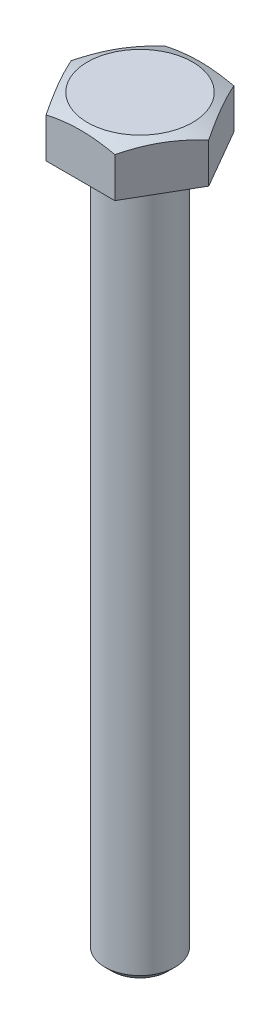
SolidWorks part; units mm, degrees
ref_plane "前视基准面" through (0, 0, 0) normal (0, 0, 1) x (1, 0, 0)
ref_plane "上视基准面" through (0, 0, 0) normal (0, 1, 0) x (1, 0, 0)
ref_plane "右视基准面" through (0, 0, 0) normal (1, 0, 0) x (0, 0, -1)
sketch "草图2" plane through (0, 0, 0) normal (0, 1, 0) x (1, 0, 0)
  line L1 (9.815, 0) -> (4.9075, 8.5)
  line L2 (4.9075, 8.5) -> (-4.9075, 8.5)
  line L3 (-4.9075, 8.5) -> (-9.815, 0)
  line L4 (-9.815, 0) -> (-4.9075, -8.5)
  line L5 (-4.9075, -8.5) -> (4.9075, -8.5)
  line L6 (4.9075, -8.5) -> (9.815, 0)
  circle A0 centre (0, 0) radius 8.5 construction
  dimension "D1" = 17
extrude "凸台-拉伸1" add sketch "草图2" along normal blind 6.7
sketch "草图3" plane through (0, 0, 0) normal (0, 0, 1) x (1, 0, 0)
  line L0 (-9.815, 5.7) -> (-7.5, 6.7)
  line L1 (-9.815, 6.7) -> (-9.815, 0) construction
  line L2 (-9.815, 6.7) -> (-4.9075, 6.7) construction
  line L3 (-7.5, 6.7) -> (-9.815, 6.7)
  line L4 (-9.815, 6.7) -> (-9.815, 5.7)
  line L5 (0, 0) -> (0, 6.7) construction
  line L6 (-4.9075, 0) -> (4.9075, 0) construction
  line L7 (-4.9075, 6.7) -> (4.9075, 6.7) construction
  dimension "D1" = 1
  dimension "D2" = 15
revolve "切除-旋转1" cut sketch "草图3" angle 360 about L5
sketch "草图4" plane through (0, 0, 0) normal (0, -1, 0) x (1, 0, 0)
  circle A0 centre (0, 0) radius 5
  dimension "D1" = 10
extrude "凸台-拉伸2" add sketch "草图4" along normal blind 100
chamfer "倒角1" distance 1 angle 45 1 edges at (0, -100, -5)
